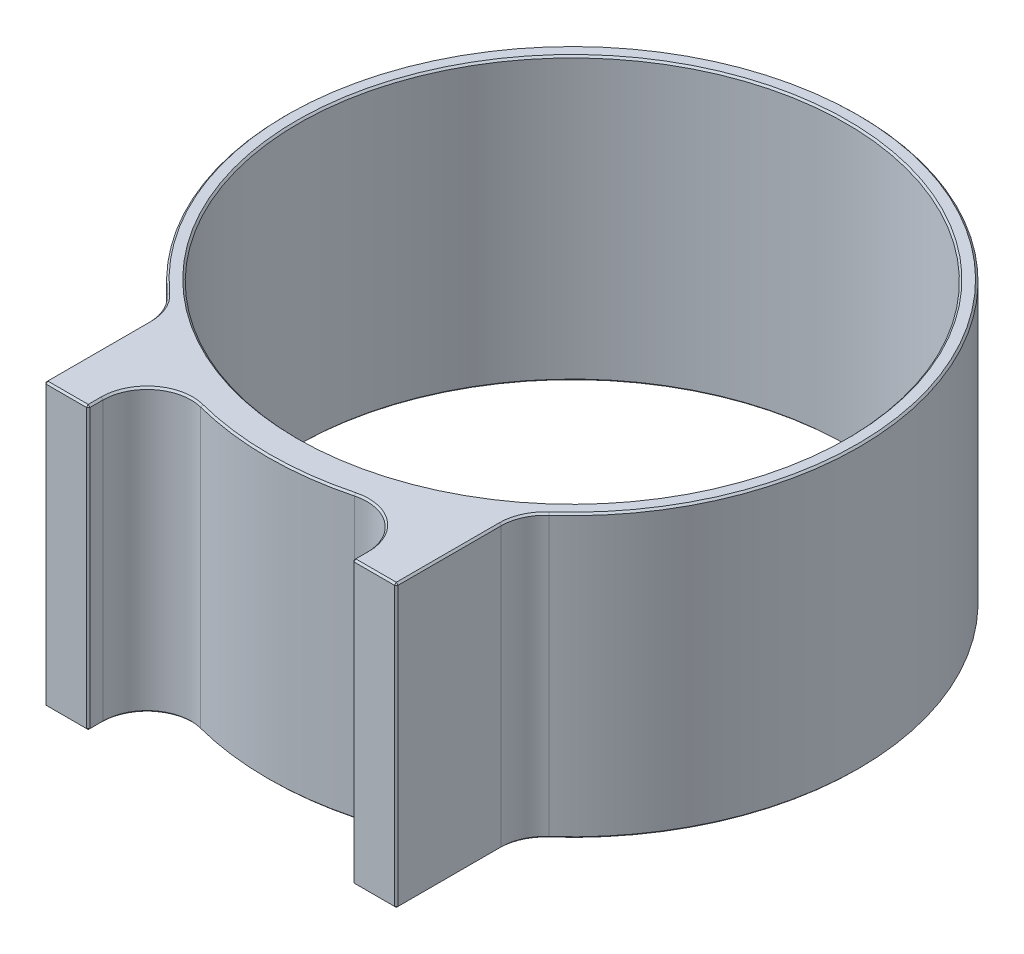
SolidWorks part; units mm, degrees
ref_plane "前视基准面" through (0, 0, 0) normal (0, 0, 1) x (1, 0, 0)
ref_plane "上视基准面" through (0, 0, 0) normal (0, 1, 0) x (1, 0, 0)
ref_plane "右视基准面" through (0, 0, 0) normal (1, 0, 0) x (0, 0, -1)
other "Configuration Table"
sketch "草图1" plane through (0, 0, 0) normal (0, 1, 0) x (1, 0, 0)
  line L2 (-40, -51.4883) -> (-40, -80)
  line L3 (-40, -80) -> (40, -80)
  line L4 (40, -51.4883) -> (40, -80)
  circle A0 centre (0, 0) radius 62.2
  arc A1 (40, -51.4883) -> (-40, -51.4883) centre (0, 0) ccw
  circle A3 centre (0, 0) radius 65.2 construction
  point P5 (67.2, 0)
  point P9 (0, -80)
  dimension "D1" = 124.4
  dimension "D3" = 0
  dimension "D5" = 80
  dimension "D6" = 80
  dimension "D2" = 3
extrude "凸台-拉伸2" add sketch "草图1" along normal blind 64
sketch "草图2" plane through (0, 64, 0) normal (0, 1, 0) x (1, 0, 0)
  line L0 (-40, -80) -> (40, -80) construction
  line L1 (-30, -80) -> (30, -80)
  line L2 (-30, -80) -> (-30, -62.3766)
  line L4 (30, -80) -> (30, -62.3766)
  arc A0 (-30, -62.3766) -> (30, -62.3766) centre (0, 0) ccw
  point P9 (0, -80)
  dimension "D1" = 60
  dimension "D2" = 0
extrude "切除-拉伸1" cut sketch "草图2" against normal through all
fillet "圆角1" radius 10 4 edges at (-30, 32, 62.3766) (30, 32, 62.3766) (40, 32, 51.4883) (-40, 32, 51.4883)
chamfer "倒角1" distance 0.4 angle 45 30 edges at (0, 0, 62.2) (35, 0, 80) (40, 0, 68.0849) (40.8761, 0, 52.0764) (0, 0, -65.2) (-40.8761, 0, 52.0764) (-40, 0, 68.0849) (-35, 0, 80) (-30, 0, 78.3248) (-26.1136, 0, 68.7361) (0, 0, 69.2159) (26.1136, 0, 68.7361) (30, 0, 78.3248) (0, 64, 62.2) (-35, 64, 80) (-40, 64, 68.0849) (-40.8761, 64, 52.0764) (0, 64, -65.2) (40.8761, 64, 52.0764) (40, 64, 68.0849) (35, 64, 80) (30, 64, 78.3248) (26.1136, 64, 68.7361) (0, 64, 69.2159) (-26.1136, 64, 68.7361) (-30, 64, 78.3248) (-40, 32, 80) (-30, 32, 80) (30, 32, 80) (40, 32, 80)
